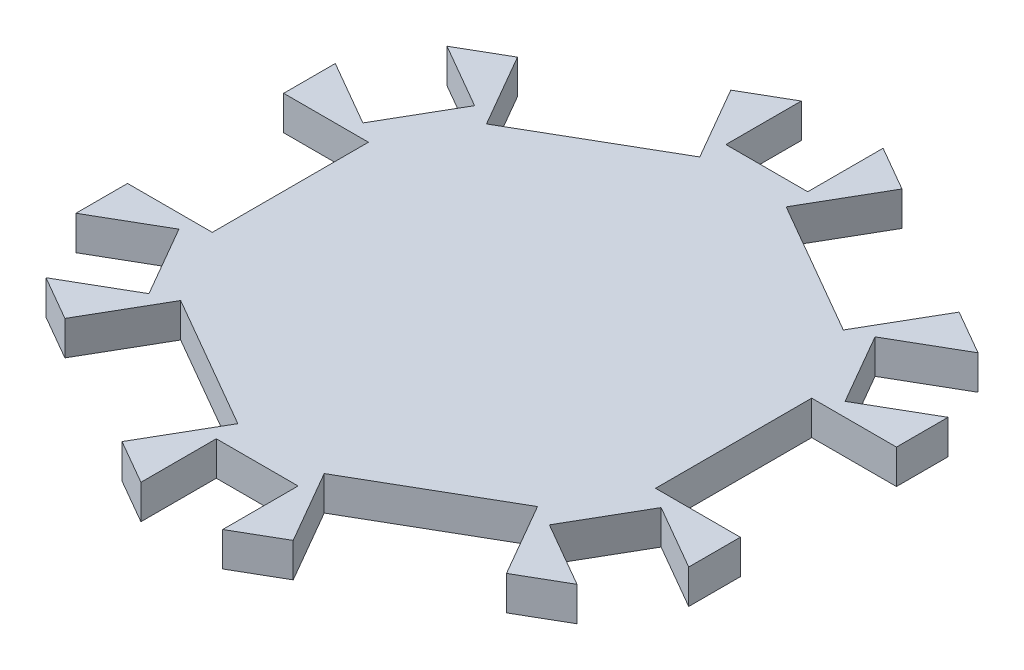
SolidWorks part; units mm, degrees
ref_plane "Front Plane" through (0, 0, 0) normal (0, 0, 1) x (1, 0, 0)
ref_plane "Top Plane" through (0, 0, 0) normal (0, 1, 0) x (1, 0, 0)
ref_plane "Right Plane" through (0, 0, 0) normal (1, 0, 0) x (0, 0, -1)
sketch "Sketch3" plane through (0, 0, 0) normal (0, 1, 0) x (1, 0, 0)
  line L0 (-71.9615, 0) -> (-61.9615, 0) construction
  line L1 (-22.4058, 70.158) -> (-17.4058, 61.4978)
  line L2 (-49.5557, 54.483) -> (-44.5557, 45.8228)
  line L3 (-71.9615, 15.675) -> (-61.9615, 15.675)
  line L8 (-71.9615, -15.675) -> (-61.9615, -15.675)
  line L9 (-71.9615, 15.675) -> (-61.9615, 15.675)
  line L10 (-71.9615, -15.675) -> (-61.9615, -15.675)
  line L11 (-22.4058, 70.158) -> (-17.4058, 61.4978)
  line L12 (-61.8115, 35.6869) -> (-61.8115, -35.6869)
  line L13 (-61.8115, -35.6869) -> (0, -71.3738)
  line L14 (0, -71.3738) -> (61.8115, -35.6869)
  line L39 (61.8115, -35.6869) -> (61.8115, 35.6869)
  line L40 (61.8115, 35.6869) -> (0, 71.3738)
  line L41 (0, 71.3738) -> (-61.8115, 35.6869)
  line L42 (71.9615, 41.547) -> (0, 83.094)
  line L43 (0, 83.094) -> (-71.9615, 41.547)
  line L44 (-71.9615, 41.547) -> (-71.9615, -41.547)
  line L45 (-71.9615, -41.547) -> (0, -83.094)
  line L46 (0, -83.094) -> (71.9615, -41.547)
  line L47 (71.9615, -41.547) -> (71.9615, 41.547)
  line L48 (-22.4058, 70.158) -> (-8.7808, 46.5588)
  line L49 (-71.9615, 15.675) -> (-44.7115, 15.675)
  line L50 (-71.9615, 15.675) -> (-71.9615, -15.675) construction
  line L51 (-71.9615, -15.675) -> (-44.7115, -15.675)
  line L52 (-44.7115, 15.675) -> (-44.7115, -15.675)
  line L53 (-58.3365, -15.675) -> (-58.3365, 15.675) construction
  line L54 (-61.9615, 35.7735) -> (-61.9615, -35.7735) construction
  line L55 (-61.9615, -35.7735) -> (0, -71.547) construction
  line L56 (0, -71.547) -> (61.9615, -35.7735) construction
  line L57 (61.9615, -35.7735) -> (61.9615, 35.7735) construction
  line L58 (61.9615, 35.7735) -> (0, 71.547) construction
  line L59 (0, 71.547) -> (-61.9615, 35.7735) construction
  line L60 (-49.5557, 54.483) -> (-44.5557, 45.8228)
  line L61 (-35.9808, 62.3205) -> (-30.9808, 53.6603) construction
  line L62 (49.5557, 54.483) -> (44.5557, 45.8228)
  line L63 (22.4058, 70.158) -> (17.4058, 61.4978)
  line L64 (49.5557, 54.483) -> (44.5557, 45.8228)
  line L65 (22.4058, 70.158) -> (17.4058, 61.4978)
  line L66 (35.9808, 62.3205) -> (30.9808, 53.6603) construction
  line L67 (71.9615, -15.675) -> (61.9615, -15.675)
  line L68 (71.9615, 15.675) -> (61.9615, 15.675)
  line L69 (71.9615, -15.675) -> (61.9615, -15.675)
  line L70 (71.9615, 15.675) -> (61.9615, 15.675)
  line L71 (71.9615, 0) -> (61.9615, 0) construction
  line L72 (22.4058, -70.158) -> (17.4058, -61.4978)
  line L73 (49.5557, -54.483) -> (44.5557, -45.8228)
  line L74 (22.4058, -70.158) -> (17.4058, -61.4978)
  line L75 (49.5557, -54.483) -> (44.5557, -45.8228)
  line L76 (35.9808, -62.3205) -> (30.9808, -53.6603) construction
  line L77 (-49.5557, -54.483) -> (-44.5557, -45.8228)
  line L78 (-22.4058, -70.158) -> (-17.4058, -61.4978)
  line L79 (-49.5557, -54.483) -> (-44.5557, -45.8228)
  line L80 (-22.4058, -70.158) -> (-17.4058, -61.4978)
  line L81 (-35.9808, -62.3205) -> (-30.9808, -53.6603) construction
  line L92 (-63.7865, 46.2668) -> (-53.7865, 40.4933)
  line L93 (-71.9615, 41.547) -> (-61.9615, 35.7735) construction
  line L94 (-71.9615, 32.1073) -> (-61.9615, 26.3338)
  line L95 (8.175, 78.3742) -> (8.175, 66.8272)
  line L96 (-8.175, 78.3742) -> (-8.175, 66.8272)
  line L97 (0, 83.094) -> (0, 71.547) construction
  line L98 (71.9615, 32.1073) -> (61.9615, 26.3338)
  line L99 (63.7865, 46.2668) -> (53.7865, 40.4933)
  line L100 (71.9615, 41.547) -> (61.9615, 35.7735) construction
  line L101 (63.7865, -46.2668) -> (53.7865, -40.4933)
  line L102 (71.9615, -32.1073) -> (61.9615, -26.3338)
  line L103 (71.9615, -41.547) -> (61.9615, -35.7735) construction
  line L104 (-8.175, -78.3742) -> (-8.175, -66.8272)
  line L105 (8.175, -78.3742) -> (8.175, -66.8272)
  line L106 (0, -83.094) -> (0, -71.547) construction
  line L107 (-71.9615, -32.1073) -> (-61.9615, -26.3338)
  line L108 (-63.7865, -46.2668) -> (-53.7865, -40.4933)
  line L109 (-71.9615, -41.547) -> (-61.9615, -35.7735) construction
  line L110 (-71.9615, 0) -> (-44.7115, 0) construction
  line L111 (-8.7808, 46.5588) -> (-35.9307, 30.8838)
  line L112 (-49.5557, 54.483) -> (-35.9307, 30.8838)
  line L113 (49.5557, 54.483) -> (35.9307, 30.8838)
  line L114 (35.9307, 30.8838) -> (8.7808, 46.5588)
  line L115 (22.4058, 70.158) -> (8.7808, 46.5588)
  line L116 (71.9615, -15.675) -> (44.7115, -15.675)
  line L117 (44.7115, -15.675) -> (44.7115, 15.675)
  line L118 (71.9615, 15.675) -> (44.7115, 15.675)
  line L119 (22.4058, -70.158) -> (8.7808, -46.5588)
  line L120 (8.7808, -46.5588) -> (35.9307, -30.8838)
  line L121 (49.5557, -54.483) -> (35.9307, -30.8838)
  line L122 (-49.5557, -54.483) -> (-35.9307, -30.8838)
  line L123 (-35.9307, -30.8838) -> (-8.7808, -46.5588)
  line L124 (-22.4058, -70.158) -> (-8.7808, -46.5588)
  point P50 (0, 0)
  point P85 (0, 0)
  point P116 (0, 0)
  point P190 (-58.3365, 0)
  dimension "D4" = 16.35
  dimension "D1" = 6
  dimension "D5" = 6
  dimension "D3" = 31.35
  dimension "D6" = 31.35
  dimension "D7" = 27.25
  dimension "D2" = 0.15
  dimension "D8" = 6
sketch "Sketch10" plane through (0, 0, 0) normal (0, 1, 0) x (1, 0, 0)
  line L0 (-71.9615, 0) -> (-61.9615, 0) construction
  line L1 (-22.3409, 70.1955) -> (-17.3409, 61.5353) construction
  line L2 (-49.6207, 54.4455) -> (-44.6207, 45.7853) construction
  line L3 (-71.9615, 15.75) -> (-61.9615, 15.75) construction
  line L8 (-71.9615, -15.75) -> (-61.9615, -15.75) construction
  line L9 (-71.9615, 15.75) -> (-61.9615, 15.75) construction
  line L10 (-71.9615, -15.75) -> (-61.9615, -15.75) construction
  line L11 (-22.3409, 70.1955) -> (-17.3409, 61.5353) construction
  line L12 (-61.8115, 35.6869) -> (-61.8115, -35.6869)
  line L13 (-61.8115, -35.6869) -> (0, -71.3738)
  line L14 (0, -71.3738) -> (61.8115, -35.6869)
  line L39 (61.8115, -35.6869) -> (61.8115, 35.6869)
  line L40 (61.8115, 35.6869) -> (0, 71.3738)
  line L41 (0, 71.3738) -> (-61.8115, 35.6869)
  line L42 (71.9615, 41.547) -> (0, 83.094) construction
  line L43 (0, 83.094) -> (-71.9615, 41.547) construction
  line L44 (-71.9615, 41.547) -> (-71.9615, -41.547) construction
  line L45 (-71.9615, -41.547) -> (0, -83.094) construction
  line L46 (0, -83.094) -> (71.9615, -41.547) construction
  line L47 (71.9615, -41.547) -> (71.9615, 41.547) construction
  line L48 (-71.9615, 15.75) -> (-71.9615, -15.75) construction
  line L49 (-71.9615, 15.75) -> (-44.7115, 15.75)
  line L50 (-71.9615, -15.75) -> (-44.7115, -15.75)
  line L51 (-44.7115, 15.75) -> (-44.7115, -15.75)
  line L52 (-22.3409, 70.1955) -> (-8.7159, 46.5963)
  line L53 (-49.6207, 54.4455) -> (-35.9957, 30.8463)
  line L54 (-61.9615, 35.7735) -> (-61.9615, -35.7735) construction
  line L55 (-61.9615, -35.7735) -> (0, -71.547) construction
  line L56 (0, -71.547) -> (61.9615, -35.7735) construction
  line L57 (61.9615, -35.7735) -> (61.9615, 35.7735) construction
  line L58 (61.9615, 35.7735) -> (0, 71.547) construction
  line L59 (0, 71.547) -> (-61.9615, 35.7735) construction
  line L60 (-49.6207, 54.4455) -> (-44.6207, 45.7853) construction
  line L61 (-35.9808, 62.3205) -> (-30.9808, 53.6603) construction
  line L62 (49.6207, 54.4455) -> (44.6207, 45.7853) construction
  line L63 (22.3409, 70.1955) -> (17.3409, 61.5353) construction
  line L64 (49.6207, 54.4455) -> (44.6207, 45.7853) construction
  line L65 (22.3409, 70.1955) -> (17.3409, 61.5353) construction
  line L66 (35.9808, 62.3205) -> (30.9808, 53.6603) construction
  line L67 (71.9615, -15.75) -> (61.9615, -15.75) construction
  line L68 (71.9615, 15.75) -> (61.9615, 15.75) construction
  line L69 (71.9615, -15.75) -> (61.9615, -15.75) construction
  line L70 (71.9615, 15.75) -> (61.9615, 15.75) construction
  line L71 (71.9615, 0) -> (61.9615, 0) construction
  line L72 (22.3409, -70.1955) -> (17.3409, -61.5353) construction
  line L73 (49.6207, -54.4455) -> (44.6207, -45.7853) construction
  line L74 (22.3409, -70.1955) -> (17.3409, -61.5353) construction
  line L75 (49.6207, -54.4455) -> (44.6207, -45.7853) construction
  line L76 (35.9808, -62.3205) -> (30.9808, -53.6603) construction
  line L77 (-49.6207, -54.4455) -> (-44.6207, -45.7853) construction
  line L78 (-22.3409, -70.1955) -> (-17.3409, -61.5353) construction
  line L79 (-49.6207, -54.4455) -> (-44.6207, -45.7853) construction
  line L80 (-22.3409, -70.1955) -> (-17.3409, -61.5353) construction
  line L81 (-35.9808, -62.3205) -> (-30.9808, -53.6603) construction
  line L92 (-63.7115, 46.3101) -> (-53.7115, 40.5366) construction
  line L93 (-71.9615, 41.547) -> (-61.9615, 35.7735) construction
  line L94 (-71.9615, 32.0207) -> (-61.9615, 26.2472) construction
  line L95 (8.25, 78.3309) -> (8.25, 66.7839) construction
  line L96 (-8.25, 78.3309) -> (-8.25, 66.7839) construction
  line L97 (0, 83.094) -> (0, 71.547) construction
  line L98 (71.9615, 32.0207) -> (61.9615, 26.2472) construction
  line L99 (63.7115, 46.3101) -> (53.7115, 40.5366) construction
  line L100 (71.9615, 41.547) -> (61.9615, 35.7735) construction
  line L101 (63.7115, -46.3101) -> (53.7115, -40.5366) construction
  line L102 (71.9615, -32.0207) -> (61.9615, -26.2472) construction
  line L103 (71.9615, -41.547) -> (61.9615, -35.7735) construction
  line L104 (-8.25, -78.3309) -> (-8.25, -66.7839) construction
  line L105 (8.25, -78.3309) -> (8.25, -66.7839) construction
  line L106 (0, -83.094) -> (0, -71.547) construction
  line L107 (-71.9615, -32.0207) -> (-61.9615, -26.2472) construction
  line L108 (-63.7115, -46.3101) -> (-53.7115, -40.5366) construction
  line L109 (-71.9615, -41.547) -> (-61.9615, -35.7735) construction
  line L110 (-8.7159, 46.5963) -> (-35.9957, 30.8463)
  line L111 (49.6207, 54.4455) -> (35.9957, 30.8463)
  line L112 (22.3409, 70.1955) -> (8.7159, 46.5963)
  line L113 (35.9957, 30.8463) -> (8.7159, 46.5963)
  line L114 (71.9615, -15.75) -> (44.7115, -15.75)
  line L115 (71.9615, 15.75) -> (44.7115, 15.75)
  line L116 (44.7115, -15.75) -> (44.7115, 15.75)
  line L117 (22.3409, -70.1955) -> (8.7159, -46.5963)
  line L118 (49.6207, -54.4455) -> (35.9957, -30.8463)
  line L119 (8.7159, -46.5963) -> (35.9957, -30.8463)
  line L120 (-49.6207, -54.4455) -> (-35.9957, -30.8463)
  line L121 (-22.3409, -70.1955) -> (-8.7159, -46.5963)
  line L122 (-35.9957, -30.8463) -> (-8.7159, -46.5963)
  point P50 (0, 0)
  point P85 (0, 0)
  point P114 (0, 0)
  dimension "D4" = 16.5
  dimension "D1" = 0.15
  dimension "D5" = 6
  dimension "D3" = 31.5
  dimension "D2" = 27.25
extrude "Boss-Extrude3" add sketch "Sketch10" along normal blind 6.9 contours L120 L122 L121 L13 L14 L117 L119 L118 L39 L114 L116 L115 L40 L111 L113 L112 L41 L52 L110 L53 L12 L49 L51 L50
sketch "Sketch11" plane through (0, 6.9, 0) normal (0, 1, 0) x (1, 0, 0)
  line L0 (-61.8115, 35.6869) -> (61.8115, -35.6869) construction
  line L1 (-63.7115, 46.3101) -> (-40.3922, 32.8467)
  line L3 (-71.9615, 32.0207) -> (-48.6422, 18.5573)
  line L5 (-40.3922, 32.8467) -> (-48.6422, 18.5573)
  line L6 (-71.9615, 41.547) -> (-71.9615, -41.547) construction
  line L7 (0, -83.094) -> (71.9615, -41.547)
  line L8 (71.9615, -41.547) -> (71.9615, 41.547)
  line L9 (71.9615, 41.547) -> (0, 83.094)
  line L10 (0, 83.094) -> (-71.9615, 41.547)
  line L11 (-71.9615, 41.547) -> (-71.9615, -41.547)
  line L12 (-71.9615, -41.547) -> (0, -83.094)
  line L13 (8.25, 78.3309) -> (8.25, 51.404)
  line L14 (-8.25, 78.3309) -> (-8.25, 51.404)
  line L15 (8.25, 51.404) -> (-8.25, 51.404)
  line L16 (71.9615, 32.0207) -> (48.6422, 18.5573)
  line L17 (63.7115, 46.3101) -> (40.3922, 32.8467)
  line L18 (48.6422, 18.5573) -> (40.3922, 32.8467)
  line L19 (63.7115, -46.3101) -> (40.3922, -32.8467)
  line L20 (71.9615, -32.0207) -> (48.6422, -18.5573)
  line L21 (40.3922, -32.8467) -> (48.6422, -18.5573)
  line L22 (-8.25, -78.3309) -> (-8.25, -51.404)
  line L23 (8.25, -78.3309) -> (8.25, -51.404)
  line L24 (-8.25, -51.404) -> (8.25, -51.404)
  line L25 (-71.9615, -32.0207) -> (-48.6422, -18.5573)
  line L26 (-63.7115, -46.3101) -> (-40.3922, -32.8467)
  line L27 (-48.6422, -18.5573) -> (-40.3922, -32.8467)
  circle A0 centre (0, 0) radius 71.9615 construction
  point P41 (0, 0)
  line M7 (-17.2659, -61.4054) -> (0, -71.3738)
  line M8 (0, -71.3738) -> (17.2659, -61.4054)
  line M12 (44.5457, -45.6554) -> (61.8115, -35.6869)
  line M13 (61.8115, -35.6869) -> (61.8115, -15.75)
  line M17 (61.8115, 15.75) -> (61.8115, 35.6869)
  line M18 (61.8115, 35.6869) -> (44.5457, 45.6554)
  line M22 (17.2659, 61.4054) -> (0, 71.3738)
  line M23 (0, 71.3738) -> (-17.2659, 61.4054)
  line M27 (-44.5457, 45.6554) -> (-61.8115, 35.6869)
  line M28 (-61.8115, 35.6869) -> (-61.8115, 15.75)
  line M32 (-61.8115, -15.75) -> (-61.8115, -35.6869)
  line M33 (-61.8115, -35.6869) -> (-44.5457, -45.6554)
  dimension "D1" = 16.5
  dimension "D2" = 6
  dimension "D3" = 31.69
extrude "Cut-Extrude1" cut sketch "Sketch11" against normal blind 10 contours L5 L1 L3 M27 M28 | L15 L13 L14 M22 M23 | L18 L16 L17 M17 M18 | L21 L19 L20 M12 M13 | L24 L22 L23 M7 M8 | L27 L25 L26 M32 M33
sketch "Sketch12" plane through (0, 6.9, 0) normal (0, 1, 0) x (1, 0, 0)
  line L0 (-44.7115, 15.75) -> (-44.7115, -15.75) construction
  circle A0 centre (0, 0) radius 44.7115 construction
  circle A1 centre (0, 0) radius 38.7115
  dimension "D1" = 6
